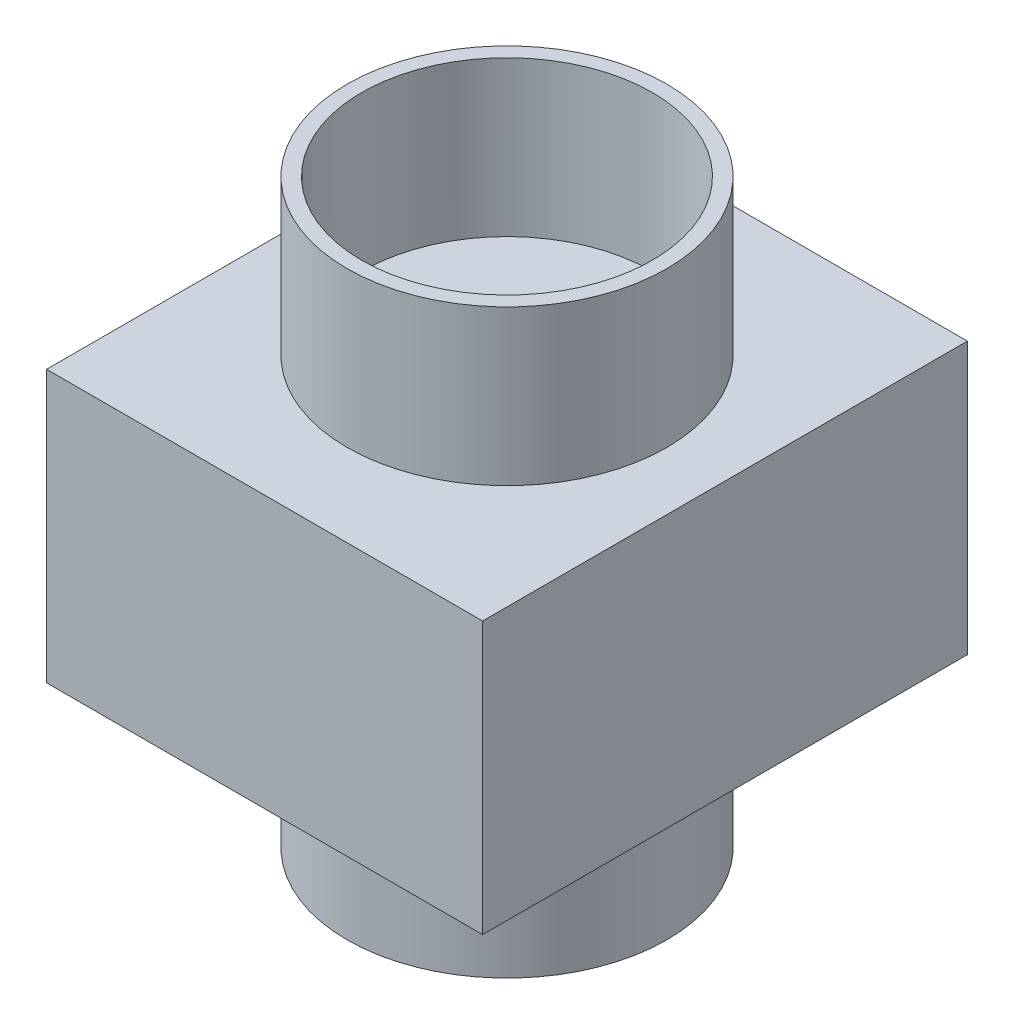
SolidWorks part; units mm, degrees
ref_plane "Front Plane" through (0, 0, 0) normal (0, 0, 1) x (1, 0, 0)
ref_plane "Top Plane" through (0, 0, 0) normal (0, 1, 0) x (1, 0, 0)
ref_plane "Right Plane" through (0, 0, 0) normal (1, 0, 0) x (0, 0, -1)
sketch "Sketch1" plane through (0, 0, 0) normal (0, 1, 0) x (1, 0, 0)
  circle A0 centre (0, 0) radius 10
  circle A1 centre (0, 0) radius 11
  dimension "D1" = 20
  dimension "D2" = 22
extrude "Boss-Extrude1" add sketch "Sketch1" along normal mid plane 40
sketch "Sketch2" plane through (0, 0, 0) normal (1, 0, 0) x (0, 0, -1)
  line L1 (16.679, 9.3436) -> (-16.679, 9.3436)
  line L2 (16.679, 9.3436) -> (16.679, -9.3436)
  line L3 (16.679, -9.3436) -> (-16.679, -9.3436)
  line L4 (-16.679, 9.3436) -> (-16.679, -9.3436)
  line L5 (16.679, 9.3436) -> (-16.679, -9.3436) construction
  line L6 (16.679, -9.3436) -> (-16.679, 9.3436) construction
  point P0 (0, 0)
extrude "Boss-Extrude2" add sketch "Sketch2" along normal mid plane 30
